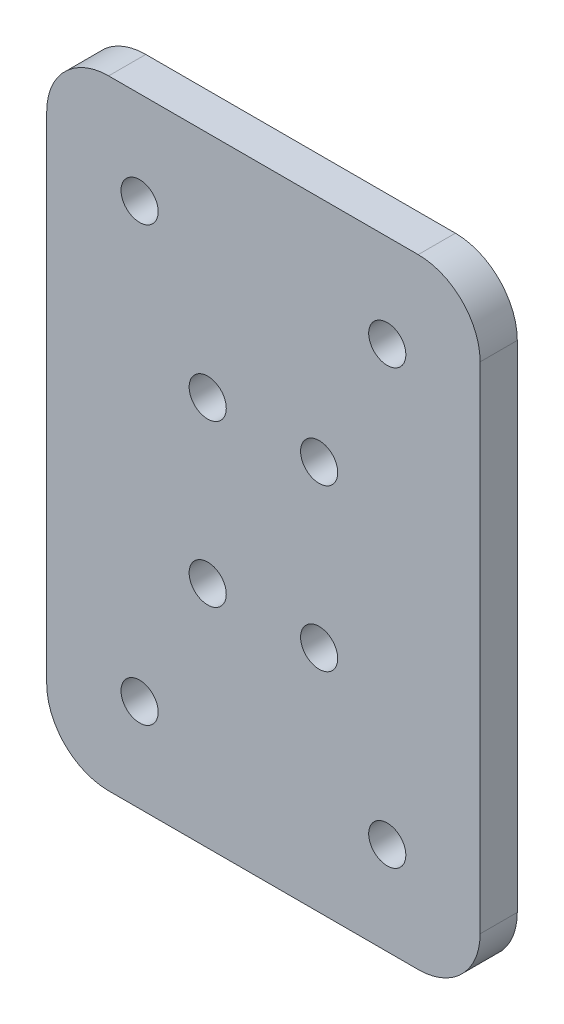
SolidWorks part; units mm, degrees
material "Thornel Mat VMA"
ref_plane "前视基准面" through (0, 0, 0) normal (0, 0, 1) x (1, 0, 0)
ref_plane "上视基准面" through (0, 0, 0) normal (0, 1, 0) x (1, 0, 0)
ref_plane "右视基准面" through (0, 0, 0) normal (1, 0, 0) x (0, 0, -1)
sketch "草图2" plane through (0, 0, 0) normal (0, 0, 1) x (1, 0, 0)
  line L1 (-10, 17.5) -> (10, 17.5) construction
  line L2 (-10, 17.5) -> (-10, -17.5) construction
  line L3 (-10, -17.5) -> (10, -17.5) construction
  line L4 (10, 17.5) -> (10, -17.5) construction
  line L5 (-10, 17.5) -> (10, -17.5) construction
  line L6 (-10, -17.5) -> (10, 17.5) construction
  line L7 (-4.5, 6.5) -> (4.5, 6.5) construction
  line L8 (-4.5, 6.5) -> (-4.5, -6.5) construction
  line L9 (-4.5, -6.5) -> (4.5, -6.5) construction
  line L10 (4.5, 6.5) -> (4.5, -6.5) construction
  line L11 (-4.5, 6.5) -> (4.5, -6.5) construction
  line L12 (-4.5, -6.5) -> (4.5, 6.5) construction
  line L13 (-17.5, 25) -> (17.5, 25)
  line L14 (-17.5, 25) -> (-17.5, -25)
  line L15 (-17.5, -25) -> (17.5, -25)
  line L16 (17.5, 25) -> (17.5, -25)
  line L17 (-17.5, 25) -> (17.5, -25) construction
  line L18 (-17.5, -25) -> (17.5, 25) construction
  circle A0 centre (-10, -17.5) radius 1.5
  circle A1 centre (10, -17.5) radius 1.5
  circle A2 centre (10, 17.5) radius 1.5
  circle A3 centre (-10, 17.5) radius 1.5
  circle A4 centre (4.5, 6.5) radius 1.5
  circle A5 centre (-4.5, 6.5) radius 1.5
  circle A6 centre (-4.5, -6.5) radius 1.5
  circle A7 centre (4.5, -6.5) radius 1.5
  point P0 (0, 0)
  point P5 (0, 0)
  point P19 (0, 0)
  dimension "D5" = 3
  dimension "D6" = 3
  dimension "D7" = 3
  dimension "D8" = 3
  dimension "D9" = 3
  dimension "D10" = 3
  dimension "D11" = 3
  dimension "D12" = 3
  dimension "D1" = 35
  dimension "D2" = 20
  dimension "D3" = 13
  dimension "D4" = 9
  dimension "D13" = 50
  dimension "D14" = 35
extrude "凸台-拉伸2" add sketch "草图2" along normal blind 3
fillet "圆角2" radius 5 4 edges at (17.5, -25, 1.5) (-17.5, -25, 1.5) (17.5, 25, 1.5) (-17.5, 25, 1.5)
